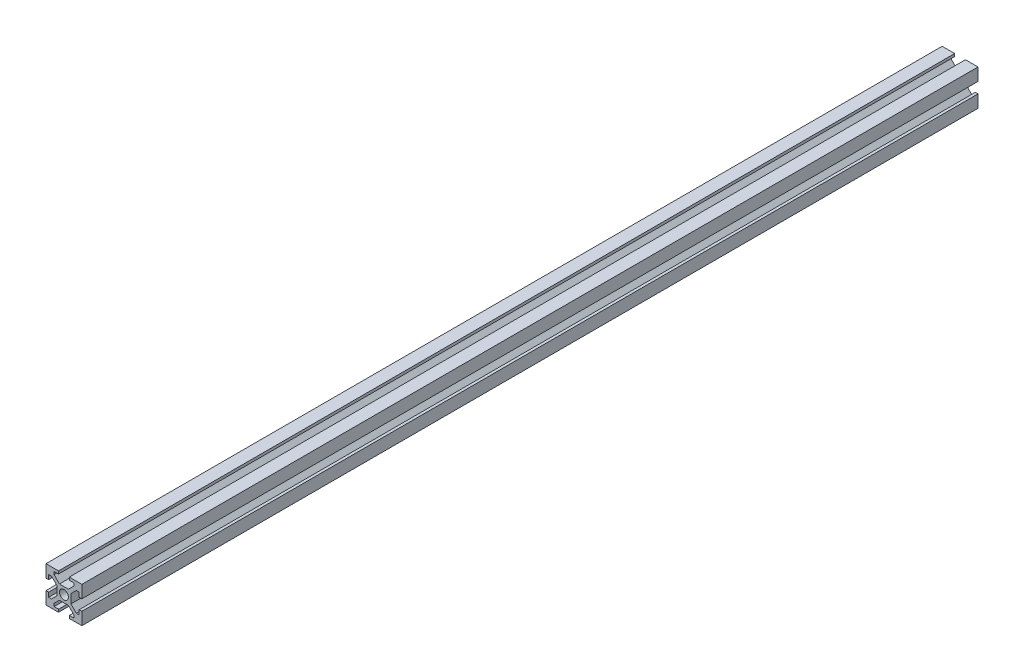
SolidWorks part; units mm, degrees
ref_plane "Front Plane" through (0, 0, 0) normal (0, 0, 1) x (1, 0, 0)
ref_plane "Top Plane" through (0, 0, 0) normal (0, 1, 0) x (1, 0, 0)
ref_plane "Right Plane" through (0, 0, 0) normal (1, 0, 0) x (0, 0, -1)
sketch "Sketch1" plane through (0, 0, 0) normal (0, 0, 1) x (1, 0, 0)
  line L0 (-10, 3) -> (-10, 10)
  line L1 (10, -10) -> (-10, -10) construction
  line L2 (10, -10) -> (10, 10) construction
  line L3 (10, 10) -> (-10, 10) construction
  line L4 (-10, -10) -> (-10, 10) construction
  line L5 (10, -10) -> (-10, 10) construction
  line L6 (10, 10) -> (-10, -10) construction
  line L7 (-10, 10) -> (-3, 10)
  line L8 (-3, 10) -> (-3, 8.5)
  line L9 (-3, 8.5) -> (-5.5, 8.5)
  line L10 (-5.5, 8.5) -> (-5.5, 6.9142)
  line L11 (-5.5, 6.9142) -> (-2.5, 3.9142)
  line L12 (0, 14.0643) -> (0, -17.0468) construction
  line L13 (-2.5, 3.9142) -> (2.5, 3.9142)
  line L14 (-10, 3) -> (-8.5, 3)
  line L15 (-8.5, 3) -> (-8.5, 5.5)
  line L16 (-8.5, 5.5) -> (-6.9142, 5.5)
  line L17 (-6.9142, 5.5) -> (-3.9142, 2.5)
  line L18 (-3.9142, 2.5) -> (-3.9142, -2.5)
  line L19 (-10, -10) -> (-10, -3)
  line L20 (-10, -3) -> (-8.5, -3)
  line L21 (-8.5, -3) -> (-8.5, -5.5)
  line L22 (-8.5, -5.5) -> (-6.9142, -5.5)
  line L23 (-6.9142, -5.5) -> (-3.9142, -2.5)
  line L24 (-10, -10) -> (-3, -10)
  line L25 (-3, -10) -> (-3, -8.5)
  line L26 (-3, -8.5) -> (-5.5, -8.5)
  line L27 (-5.5, -8.5) -> (-5.5, -6.9142)
  line L28 (10, 0) -> (-10, 0) construction
  line L29 (-5.5, -6.9142) -> (-2.5, -3.9142)
  line L30 (-2.5, -3.9142) -> (2.5, -3.9142)
  line L31 (5.5, -6.9142) -> (2.5, -3.9142)
  line L32 (5.5, -8.5) -> (5.5, -6.9142)
  line L33 (3, -8.5) -> (5.5, -8.5)
  line L34 (3, -10) -> (3, -8.5)
  line L35 (10, -10) -> (3, -10)
  line L36 (6.9142, -5.5) -> (3.9142, -2.5)
  line L37 (8.5, -5.5) -> (6.9142, -5.5)
  line L38 (8.5, -3) -> (8.5, -5.5)
  line L39 (10, -3) -> (8.5, -3)
  line L40 (10, -10) -> (10, -3)
  line L41 (3.9142, 2.5) -> (3.9142, -2.5)
  line L42 (6.9142, 5.5) -> (3.9142, 2.5)
  line L43 (8.5, 5.5) -> (6.9142, 5.5)
  line L44 (8.5, 3) -> (8.5, 5.5)
  line L45 (10, 3) -> (8.5, 3)
  line L46 (5.5, 6.9142) -> (2.5, 3.9142)
  line L47 (5.5, 8.5) -> (5.5, 6.9142)
  line L48 (3, 8.5) -> (5.5, 8.5)
  line L49 (3, 10) -> (3, 8.5)
  line L50 (10, 10) -> (3, 10)
  line L51 (10, 3) -> (10, 10)
  circle A0 centre (0, 0) radius 2.5
  point P0 (0, 0)
  point P30 (0, 0)
  point P33 (0, -3.9142)
  point P49 (0, 3.9142)
  point P55 (-10, 0)
  dimension "D10" = 5
  dimension "D1" = 20
  dimension "D2" = 20
  dimension "D3" = 7
  dimension "D5" = 1.5
  dimension "D6" = 1
  dimension "D8" = 5
  dimension "D9" = 4.5
extrude "Boss-Extrude1" add sketch "Sketch1" against normal blind 500
